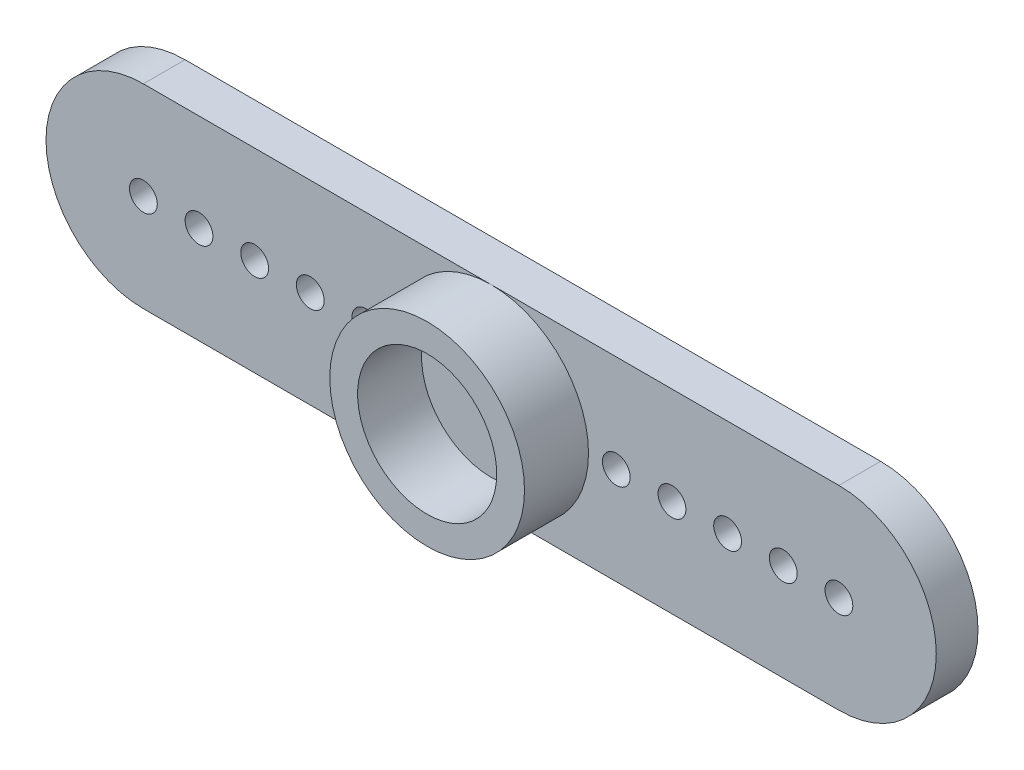
SolidWorks part; units mm, degrees
ref_plane "Alzado" through (0, 0, 0) normal (0, 0, 1) x (1, 0, 0)
ref_plane "Planta" through (0, 0, 0) normal (0, 1, 0) x (1, 0, 0)
ref_plane "Vista lateral" through (0, 0, 0) normal (1, 0, 0) x (0, 0, -1)
sketch "Croquis1" plane through (0, 0, 0) normal (0, 0, 1) x (1, 0, 0)
  line L0 (0, 0) -> (25, 0) construction
  line L1 (0, 3.5) -> (25, 3.5)
  line L2 (0, -3.5) -> (25, -3.5)
  arc A0 (0, 3.5) -> (0, -3.5) centre (0, 0) ccw
  arc A1 (25, -3.5) -> (25, 3.5) centre (25, 0) ccw
  point P3 (12.5, 0)
  dimension "D1" = 32
  dimension "D2" = 3.5
extrude "Saliente-Extruir1" add sketch "Croquis1" along normal blind 1.5
sketch "Croquis2" plane through (0, 0, 1.5) normal (0, 0, 1) x (1, 0, 0)
  line L0 (25, 3.5) -> (0, 3.5) construction
  line L1 (0, -3.5) -> (25, -3.5) construction
  circle A0 centre (12.5, 0) radius 3.5
  circle A1 centre (12.5, 0) radius 2.5
  point P5 (12.5, 3.5)
  dimension "D1" = 5
extrude "Saliente-Extruir2" add sketch "Croquis2" along normal blind 2.3
sketch "Croquis4" plane through (0, 0, 0) normal (0, 0, -1) x (-1, 0, 0)
  line L0 (-28.5, 0) -> (3.5, 0) construction
  line L1 (-12.5, 0) -> (-12.5, 3.5) construction
  line L2 (-25, 3.5) -> (0, 3.5) construction
  arc A0 (-25, 3.5) -> (-25, -3.5) centre (-25, 0) ccw construction
  arc A1 (0, -3.5) -> (0, 3.5) centre (0, 0) ccw construction
  circle A2 centre (0, 0) radius 0.5
  circle A3 centre (-25, 0) radius 0.5
  dimension "D1" = 1
  dimension "D2" = 25
extrude "Cortar-Extruir1" cut sketch "Croquis4" against normal through all
sketch "Croquis5" plane through (0, 0, 0) normal (0, 0, -1) x (-1, 0, 0)
  line L0 (-12.5, 3.5) -> (-12.5, -3.5) construction
  line L1 (-25, 3.5) -> (0, 3.5) construction
  line L2 (0, -3.5) -> (-25, -3.5) construction
  line L3 (-12.5, 0) -> (-8, 0) construction
  circle A0 centre (-8, 0) radius 0.5
  circle A1 centre (0, 0) radius 0.5 construction
  circle A2 centre (-6, 0) radius 0.5
  circle A3 centre (-4, 0) radius 0.5
  circle A4 centre (-2, 0) radius 0.5
  circle A5 centre (-23, 0) radius 0.5
  circle A6 centre (-21, 0) radius 0.5
  circle A7 centre (-19, 0) radius 0.5
  circle A8 centre (-17, 0) radius 0.5
  dimension "D1" = 4.5
  dimension "D3" = 2
  dimension "D2" = 4
extrude "Cortar-Extruir2" cut sketch "Croquis5" against normal up to next
